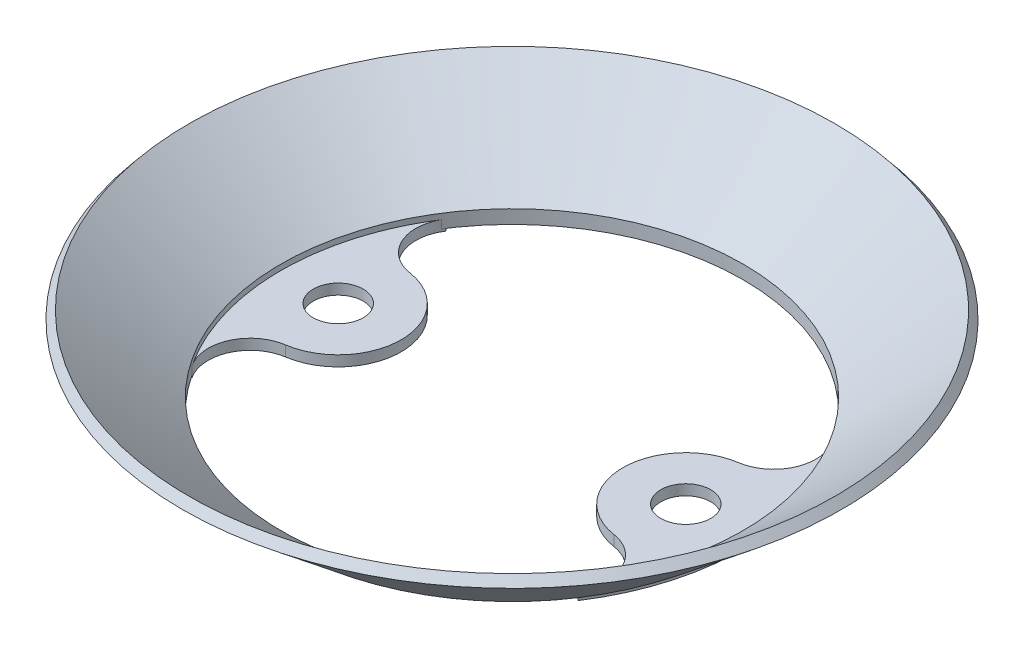
SolidWorks part; units mm, degrees
material "AISI 1020"
ref_plane "Plan de face" through (0, 0, 0) normal (0, 0, 1) x (1, 0, 0)
ref_plane "Plan de dessus" through (0, 0, 0) normal (0, 1, 0) x (1, 0, 0)
ref_plane "Plan de droite" through (0, 0, 0) normal (1, 0, 0) x (0, 0, -1)
sketch "Esquisse1" plane through (0, 0, 0) normal (1, 0, 0) x (0, 0, -1)
  line L0 (0, 0) -> (0, 17.5861) construction
  line L1 (-22, -0.7672) -> (-31.3856, 6.9608)
  line L2 (-31.3856, 6.9608) -> (-30.75, 7.7328)
  line L3 (-30.75, 7.7328) -> (-22, 0.5281)
  line L4 (-22, -0.7672) -> (-22, 0.5281)
  dimension "D1" = 8.5
  dimension "D2" = 1
  dimension "D3" = 30.75
  dimension "D4" = 22
revolve "Révolution1" add sketch "Esquisse1" angle 360 about L0
sketch "Esquisse2" plane through (0, 0, 0) normal (0, 1, 0) x (1, 0, 0)
  line L0 (50.6737, 0) -> (-50.6737, 0) construction
  line L1 (0, 0) -> (0, 22.3776) construction
  arc A0 (-15.6454, 5.9314) -> (-15.6454, -5.9314) centre (-16.55, 0) cw
  circle A2 centre (0, 0) radius 22 construction
  arc A3 (-15.6454, 5.9314) -> (-18.3851, 12.0825) centre (-15.0424, 9.8857) cw
  arc A4 (-15.6454, -5.9314) -> (-18.3851, -12.0825) centre (-15.0424, -9.8857) ccw
  circle A5 centre (-16.55, 0) radius 2.375
  circle A6 centre (16.55, 0) radius 2.375
  arc A7 (15.6454, -5.9314) -> (18.3851, -12.0825) centre (15.0424, -9.8857) cw
  arc A8 (15.6454, 5.9314) -> (15.6454, -5.9314) centre (16.55, 0) ccw
  arc A9 (15.6454, 5.9314) -> (18.3851, 12.0825) centre (15.0424, 9.8857) ccw
  circle A10 centre (0, 0) radius 22
  dimension "D1" = 6
  dimension "D3" = 4
  dimension "D4" = 4.75
  dimension "D2" = 16.55
extrude "Boss.-Extru.3" add sketch "Esquisse2" against normal blind 1 separate body contours A4 A0 A3 A10 A5 | A9 A8 A7 A10 A6
